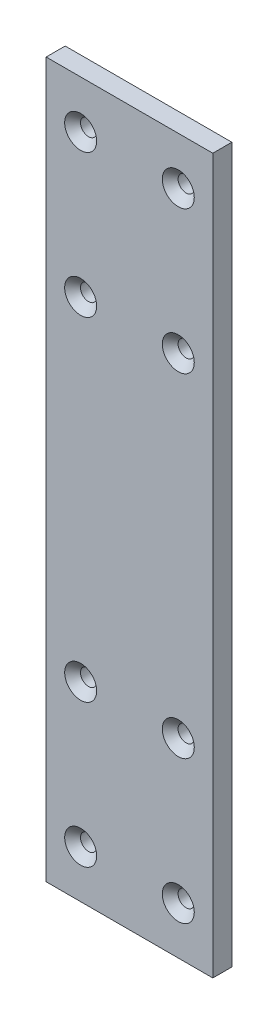
SolidWorks part; units mm, degrees
material "环氧树脂,未充填"
ref_plane "前视基准面" through (0, 0, 0) normal (0, 0, 1) x (1, 0, 0)
ref_plane "上视基准面" through (0, 0, 0) normal (0, 1, 0) x (1, 0, 0)
ref_plane "右视基准面" through (0, 0, 0) normal (1, 0, 0) x (0, 0, -1)
sketch "草图1" plane through (0, 0, 0) normal (0, 0, 1) x (1, 0, 0)
  line L1 (-17.5, 75) -> (17.5, 75)
  line L2 (-17.5, 75) -> (-17.5, -75)
  line L3 (-17.5, -75) -> (17.5, -75)
  line L4 (17.5, 75) -> (17.5, -75)
  line L5 (-17.5, 75) -> (17.5, -75) construction
  line L6 (-17.5, -75) -> (17.5, 75) construction
  point P0 (0, 0)
  dimension "D1" = 35
  dimension "D2" = 150
extrude "凸台-拉伸1" add sketch "草图1" along normal blind 4
sketch "草图2" plane through (0, 0, 4) normal (0, 0, 1) x (1, 0, 0)
  line L0 (0, 75) -> (0, 0) construction
  line L1 (-10.25, -35) -> (10.25, -35) construction
  line L2 (-10.25, -35) -> (-10.25, -65) construction
  line L3 (-10.25, -65) -> (10.25, -65) construction
  line L4 (10.25, -35) -> (10.25, -65) construction
  line L5 (-10.25, -35) -> (10.25, -65) construction
  line L6 (-10.25, -65) -> (10.25, -35) construction
  line L7 (17.5, 75) -> (-17.5, 75) construction
  line L8 (-17.5, 0) -> (17.5, 0) construction
  line L9 (-17.5, 75) -> (-17.5, -75) construction
  line L10 (17.5, -75) -> (17.5, 75) construction
  line L11 (-10.25, 65) -> (10.25, 35) construction
  line L12 (-10.25, 35) -> (10.25, 65) construction
  line L13 (10.25, 35) -> (10.25, 65) construction
  line L14 (-10.25, 65) -> (10.25, 65) construction
  line L15 (-10.25, 35) -> (-10.25, 65) construction
  line L16 (-10.25, 35) -> (10.25, 35) construction
  line L17 (-17.5, -75) -> (17.5, -75) construction
  circle A0 centre (-10.25, -35) radius 1.5
  circle A1 centre (-10.25, -65) radius 1.5
  circle A2 centre (10.25, -65) radius 1.5
  circle A3 centre (10.25, -35) radius 1.5
  circle A4 centre (10.25, 35) radius 1.5
  circle A5 centre (10.25, 65) radius 1.5
  circle A6 centre (-10.25, 65) radius 1.5
  circle A7 centre (-10.25, 35) radius 1.5
  point P0 (0, -50)
  point P29 (0, 50)
  point P33 (-10.25, 65)
  point P34 (-10.25, 35)
  point P35 (10.25, 35)
  point P36 (10.25, 65)
  dimension "D3" = 3
  dimension "D1" = 30
  dimension "D2" = 20.5
  dimension "D4" = 10
hole_wizard "M3 六角凹锥坑螺钉的锥形沉头孔1" positions "3D草图1" profile "草图4" countersink size "M3" standard "ISO" end condition through all
sketch3d "3D草图1"
  point P0 (-10.25, -35, 4)
  point P3 (10.25, -35, 4)
  point P6 (10.25, -65, 4)
  point P9 (-10.25, -65, 4)
  point P14 (-10.25, 65, 4)
  point P17 (10.25, 65, 4)
  point P20 (10.25, 35, 4)
  point P23 (-10.25, 35, 4)
sketch "草图4" plane through (-10.25, -35, 4) normal (1, 0, 0) x (0, -1, 0)
  line L0 (0, 0) -> (0, 4)
  line L1 (0, 4) -> (1.7, 4)
  line L2 (1.7, 4) -> (1.7, 1.66)
  line L3 (1.7, 1.66) -> (3.36, 0)
  line L5 (3.36, 0) -> (0, 0)
  line L6 (-1.7, 1.66) -> (-3.36, 0) construction
  line L11 (0, -6.35) -> (0, 107.95) construction
  dimension "通孔孔直径" = 3.4
  dimension "通孔孔深度" = 4
  dimension "近端锥形沉头孔直径" = 6.72
  dimension "近端锥形沉头孔角度" = 90
